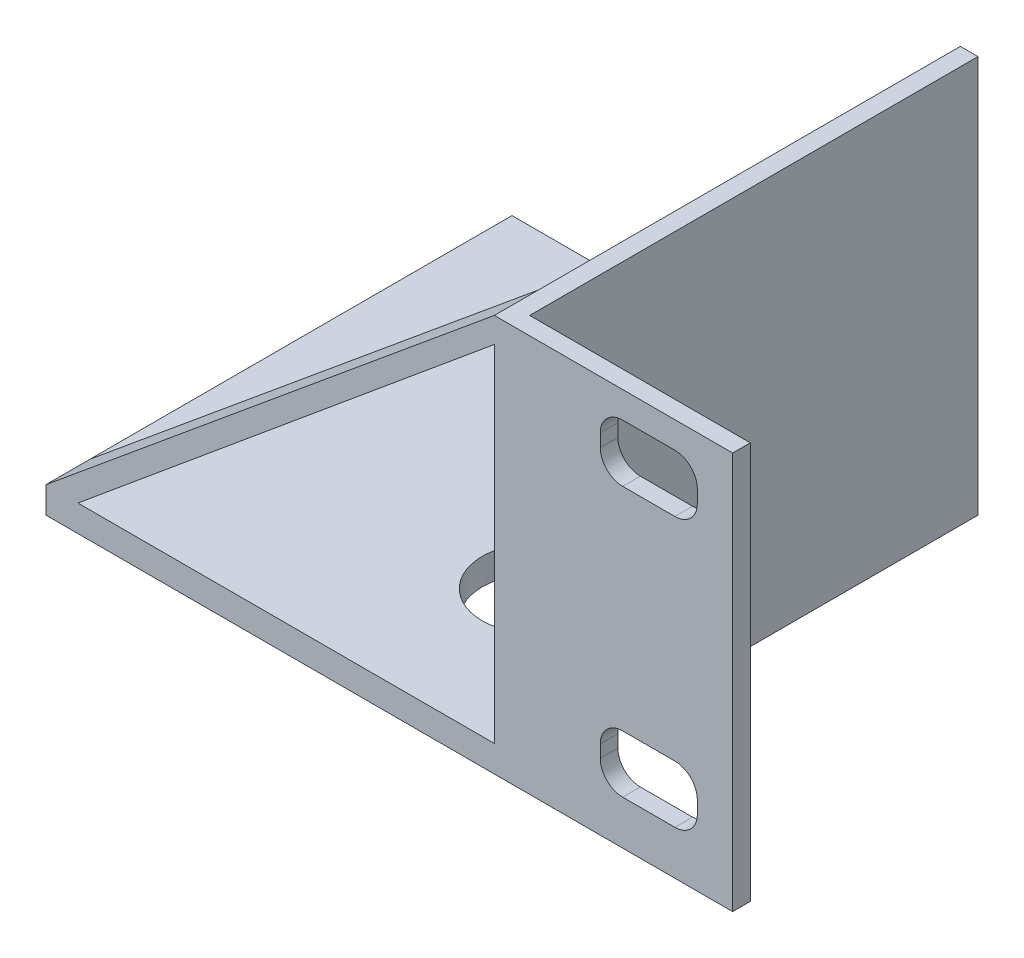
SolidWorks part; units mm, degrees
ref_plane "Front Plane" through (0, 0, 0) normal (0, 0, 1) x (1, 0, 0)
ref_plane "Top Plane" through (0, 0, 0) normal (0, 1, 0) x (1, 0, 0)
ref_plane "Right Plane" through (0, 0, 0) normal (1, 0, 0) x (0, 0, -1)
sketch "Sketch1" plane through (0, 0, 0) normal (0, 0, 1) x (1, 0, 0)
  line L1 (0, 0) -> (-25, 0)
  line L2 (0, 0) -> (0, 45)
  line L3 (0, 45) -> (-25, 45)
  line L4 (-25, 0) -> (-25, 45)
  dimension "D1" = 25
  dimension "D2" = 45
extrude "Boss-Extrude1" add sketch "Sketch1" along normal blind 2
sketch "Sketch2" plane through (0, 0, 2) normal (0, 0, 1) x (1, 0, 0)
  line L2 (-15, 11.5) -> (-15, 5)
  line L4 (-15, 5) -> (-4, 5)
  line L6 (-15, 35.5) -> (-4, 35.5)
  line L7 (-15, 42) -> (-15, 35.5)
  line L8 (-4, 35.5) -> (-4, 42)
  line L9 (-4, 42) -> (-15, 42)
  line L10 (-4, 5) -> (-4, 11.5)
  line L11 (-4, 11.5) -> (-15, 11.5)
  dimension "D1" = 24
  dimension "D2" = 6.5
  dimension "D3" = 11
  dimension "D4" = 11
extrude "Cut-Extrude1" cut sketch "Sketch2" against normal blind 19.78
fillet "Fillet1" radius 2.54 8 edges at (-15, 5, 1) (-15, 11.5, 1) (-4, 5, 1) (-4, 11.5, 1) (-4, 35.5, 1) (-4, 42, 1) (-15, 42, 1) (-15, 35.5, 1)
sketch "Sketch3" plane through (-25, 0, 0) normal (-1, 0, 0) x (0, 0, 1)
  line L1 (2, 0) -> (0, 0)
  line L2 (2, 0) -> (2, 45)
  line L3 (2, 45) -> (0, 45)
  line L5 (0, 0) -> (-50.8, 0)
  line L7 (0, 45) -> (-50.8, 45)
  line L8 (-50.8, 0) -> (-50.8, 45)
  dimension "D1" = 50.8
extrude "Boss-Extrude2" add sketch "Sketch3" along normal blind 2
sketch "Sketch4" plane through (-27, 0, 0) normal (-1, 0, 0) x (0, 0, 1)
  line L0 (2, 0) -> (2, 45) construction
  line L1 (-50.8, 0) -> (2, 0)
  line L2 (-50.8, 0) -> (-50.8, 3)
  line L3 (-50.8, 3) -> (2, 3)
  line L4 (2, 0) -> (2, 3)
  dimension "D1" = 3
extrude "Boss-Extrude3" add sketch "Sketch4" along normal blind 50.8
sketch "Sketch5" plane through (0, 0, 2) normal (0, 0, 1) x (1, 0, 0)
  line L0 (-77.8, 3) -> (-27, 45)
  line L4 (-27, 45) -> (-27, 42.1518)
  line L7 (-77.8, 3) -> (-77.8, 0)
  line L8 (-77.8, 0) -> (-27, 42.1518)
extrude "Boss-Extrude4" add sketch "Sketch5" against normal blind 5
sketch "Sketch7" plane through (0, 3, 0) normal (0, 1, 0) x (1, 0, 0)
  circle A0 centre (-39.7, 15.7) radius 6.35
  dimension "D1" = 12.7
extrude "Cut-Extrude3" cut sketch "Sketch7" against normal blind 5
